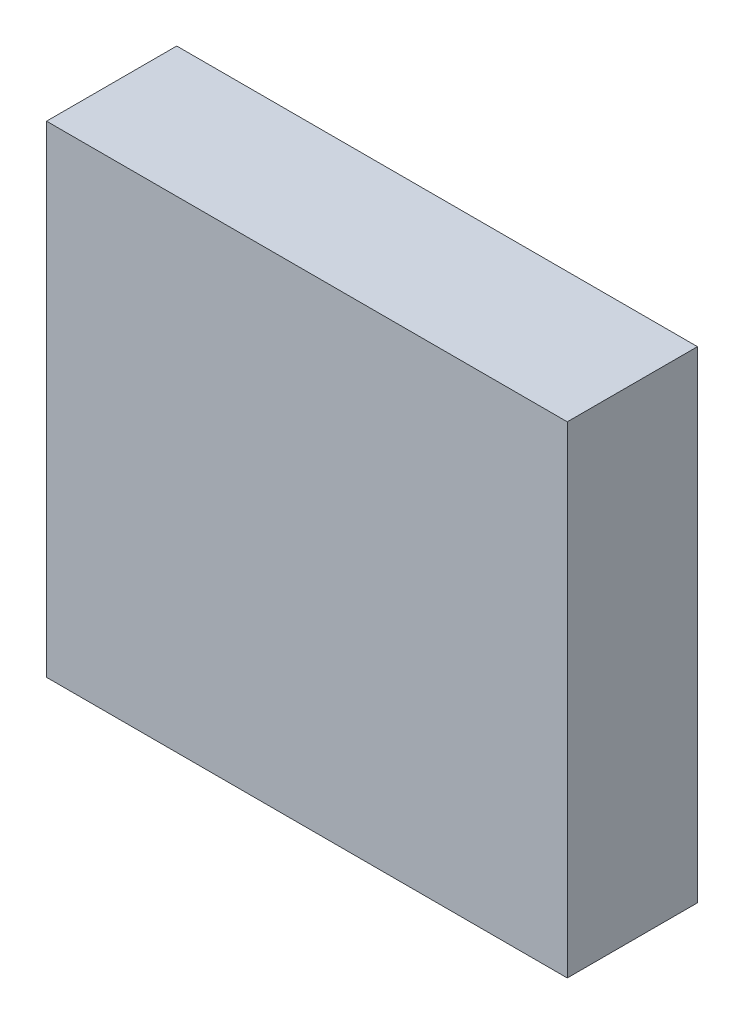
SolidWorks part; units mm, degrees
ref_plane "Front Plane" through (0, 0, 0) normal (0, 0, 1) x (1, 0, 0)
ref_plane "Top Plane" through (0, 0, 0) normal (0, 1, 0) x (1, 0, 0)
ref_plane "Right Plane" through (0, 0, 0) normal (1, 0, 0) x (0, 0, -1)
sketch "Sketch1" plane through (0, 0, 0) normal (0, 0, 1) x (1, 0, 0)
  line L1 (0, 0) -> (40, 0)
  line L2 (0, 0) -> (0, 37)
  line L3 (0, 37) -> (40, 37)
  line L4 (40, 0) -> (40, 37)
extrude "Boss-Extrude1" add sketch "Sketch1" along normal blind 10
